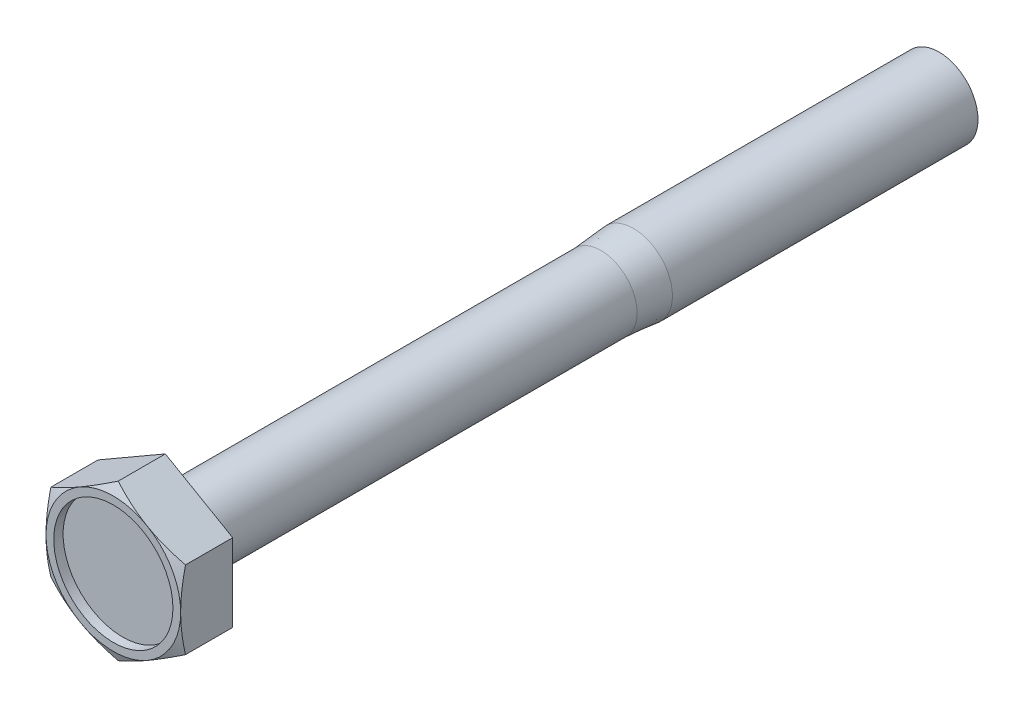
SolidWorks part; units mm, degrees
extrude "基体-拉伸" add sketch "草图3" along normal blind 2
sketch "草图3" plane through (0, 0, 0) normal (0, 0, 1) x (1, 0, 0)
  line L1 (2.5894, -1.495) -> (2.5894, 1.495)
  line L2 (2.5894, 1.495) -> (0, 2.99)
  line L3 (0, 2.99) -> (-2.5894, 1.495)
  line L4 (-2.5894, 1.495) -> (-2.5894, -1.495)
  line L5 (-2.5894, -1.495) -> (0, -2.99)
  line L6 (0, -2.99) -> (2.5894, -1.495)
  circle A0 centre (0, 0) radius 2.5894 construction
  dimension "D1" = 5.98
revolve "凸台-旋转1" add sketch "草图6"
sketch "草图6" plane through (0, 0, 0) normal (1, 0, 0) x (0, 0, -1)
  line L0 (0, 0) -> (2.3184, 0) construction
  line L2 (0, 1.3917) -> (16.75, 1.3917)
  line L3 (0, -1.495) -> (0, 1.495) construction
  line L4 (16.75, 1.3917) -> (18, 1.5)
  line L5 (18, 1.5) -> (30, 1.5)
  line L6 (30, 1.5) -> (30, 0)
  line L7 (0, 0) -> (30, 0)
  line L8 (0, 0) -> (0, 1.3917)
  dimension "D1" = 2.7835
  dimension "D2" = 3
  dimension "D3" = 1.25
  dimension "D4" = 30
  dimension "D5" = 12
cosmetic thread "螺旋线1"
revolve "切除-旋转1" cut sketch "草图7" angle 360 about L5
sketch "草图7" plane through (0, 0, 0) normal (0, 1, 0) x (1, 0, 0)
  line L0 (1.5, 30.25) -> (1.5, 29.75)
  line L1 (1.5, 29.75) -> (1.067, 30)
  line L2 (1.5, 30) -> (-1.5, 30) construction
  line L3 (1.067, 30) -> (1.5, 30.25)
  line L5 (0, 0) -> (0, 2.1791) construction
  dimension "D2" = 60
  dimension "D3" = 60
  dimension "D1" = 0.433
  dimension "D4" = 1.5
material "5.8级"
ref_plane "前视" through (0, 0, 0) normal (0, 0, 1) x (1, 0, 0)
ref_plane "上视" through (0, 0, 0) normal (0, 1, 0) x (1, 0, 0)
ref_plane "右视" through (0, 0, 0) normal (1, 0, 0) x (0, 0, -1)
sketch "尺寸草图" plane through (0, 0, 0) normal (0, 1, 0) x (1, 0, 0)
  line L0 (4.2057, 0) -> (-4.2057, 0)
  line L1 (30.1422, -1.495) -> (30.1422, 1.495)
  line L2 (30.1422, 1.495) -> (27.5527, 2.99)
  line L3 (27.5527, 2.99) -> (24.9633, 1.495)
  line L4 (24.9633, 1.495) -> (24.9633, -1.495)
  line L5 (24.9633, -1.495) -> (27.5527, -2.99)
  line L6 (27.5527, -2.99) -> (30.1422, -1.495)
  line L7 (-4.2057, 0) -> (-5.2005, 0.6605)
  line L8 (-5.2005, 0.6605) -> (-5.2005, 2)
  line L9 (-5.2005, 2) -> (-0.945, 2)
  line L10 (-0.845, 2.1) -> (-0.845, 18.75)
  line L11 (-0.845, 18.75) -> (-1.5, 20)
  line L12 (-1.5, 20) -> (-1.5, 32)
  line L13 (-1.5, 32) -> (1.5, 32)
  line L14 (1.5, 20) -> (1.5, 32)
  line L15 (0, 0) -> (0, -2.324) construction
  line L16 (0.845, 18.75) -> (1.5, 20)
  line L17 (0.845, 2.1) -> (0.845, 18.75)
  line L18 (5.2005, 2) -> (0.945, 2)
  line L19 (5.2005, 0.6605) -> (5.2005, 2)
  line L20 (4.2057, 0) -> (5.2005, 0.6605)
  circle A0 centre (27.5527, 0) radius 2.5894 construction
  circle A1 centre (27.5527, 0) radius 2.75
  arc A2 (-0.945, 2) -> (-0.845, 2.1) centre (-0.945, 2.1) ccw
  arc A3 (0.945, 2) -> (0.845, 2.1) centre (0.945, 2.1) cw
  point P26 (1.5, 32)
  point P31 (1.5, 31.5)
  point P32 (0, 12)
  dimension "s" = 5.5
sketch "草图4" plane through (0, 0, 2) normal (0, 0, 1) x (1, 0, 0)
  line L0 (-2.5894, -1.495) -> (0, -2.99) construction
  circle A0 centre (0, 0) radius 2.5894
extrude "切除-拉伸1" cut sketch "草图4" against normal blind 10 draft 65 flip side to cut
sketch "草图5" plane through (0, 0, 2) normal (0, 0, 1) x (1, 0, 0)
  circle A0 centre (0, 0) radius 2.2917
  dimension "D1" = 4.5833
extrude "切除-拉伸2" cut sketch "草图5" against normal blind 0.36
pattern_linear "阵列(线性)1" [suppressed] count 25 spacing 0.5
fillet "圆角1" radius 0.1 1 edges at (1.3917, 0, 0)
sketch "草图8" plane through (0, 0, -30) normal (0, 0, -1) x (-1, 0, 0)
  circle A0 centre (0, 0) radius 1.99
equation "\"D2@草图6\" = \"D@尺寸草图\""
equation "\"D5@草图6\" = \"b@尺寸草图\""
equation "\"D1@草图3\" = \"e@尺寸草图\""
equation "\"D1@基体-拉伸\" = \"K@尺寸草图\""
equation "\"D1@圆角1\" = \"r@尺寸草图\""
equation "\"D1@草图4\" = \"s@尺寸草图\""
equation "\"D3@草图6\" = \"x@尺寸草图\""
equation "\"D3@阵列(线性)1\" = \"P@尺寸草图\""
equation "\"D4@草图6\" = \"L@尺寸草图\""
equation "\"D1@草图5\" = \"s@尺寸草图\"*5/6"
equation "\"D1@切除-拉伸2\" = \"D1@基体-拉伸\"*0.18"
equation "\"D1@草图7\" = \"D3@阵列(线性)1\"*0.866"
equation "\"D1@草图6\" = \"D2@草图6\"-\"D1@草图7\"/2"
equation "\"D1@阵列(线性)1\" = \"D5@草图6\"/\"D3@阵列(线性)1\"+1"
equation "\"D4@草图7\" = \"D2@草图6\" / 2"
equation "\"D1@螺旋线1\" = \"D5@草图6\" + \"D3@草图6\"/2"
equation "\"D2@螺旋线1\" = \"D2@草图6\" - \"D1@草图7\"*2"
